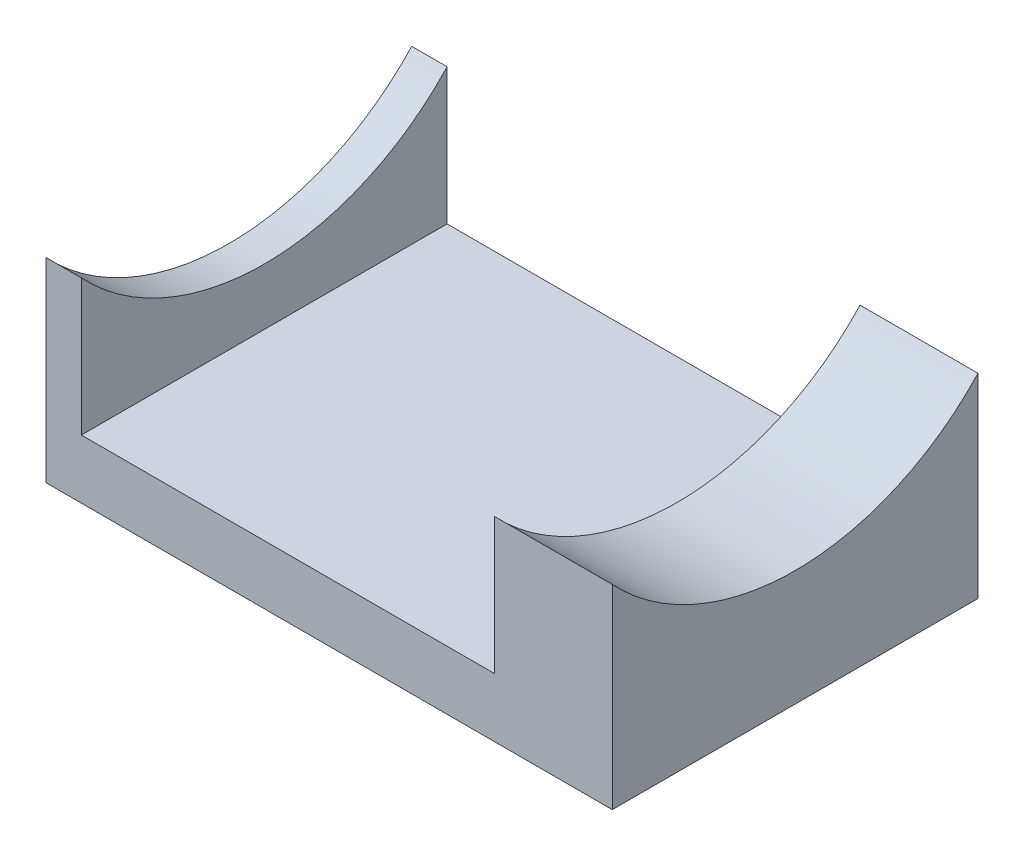
SolidWorks part; units mm, degrees
ref_plane "Piano frontale" through (0, 0, 0) normal (0, 0, 1) x (1, 0, 0)
ref_plane "Piano superiore" through (0, 0, 0) normal (0, 1, 0) x (1, 0, 0)
ref_plane "Piano destro" through (0, 0, 0) normal (1, 0, 0) x (0, 0, -1)
sketch "Schizzo1" plane through (0, 0, 0) normal (0, 0, 1) x (1, 0, 0)
  line L1 (-24, -15.5) -> (24, -15.5)
  line L2 (-24, -15.5) -> (-24, 15.5)
  line L3 (-24, 15.5) -> (24, 15.5)
  line L4 (24, -15.5) -> (24, 15.5)
  line L5 (-24, -15.5) -> (24, 15.5) construction
  line L6 (-24, 15.5) -> (24, -15.5) construction
  point P0 (0, 0)
  point P4 (0, 0)
  dimension "D1" = 48
  dimension "D2" = 31
extrude "Estrusione-Estrusione1" add sketch "Schizzo1" along normal mid plane 31
sketch "Schizzo2" plane through (0, 0, 15.5) normal (0, 0, 1) x (1, 0, 0)
  line L0 (24, 15.5) -> (-24, 15.5) construction
  line L1 (-21, 15.5) -> (14, 15.5)
  line L2 (-21, 15.5) -> (-21, -10.5)
  line L3 (-21, -10.5) -> (14, -10.5)
  line L4 (14, 15.5) -> (14, -10.5)
  line L5 (-24, -15.5) -> (24, -15.5) construction
  line L6 (-24, 15.5) -> (-24, -15.5) construction
  line L7 (24, -15.5) -> (24, 15.5) construction
  dimension "D1" = 5
  dimension "D2" = 3
  dimension "D3" = 10
extrude "Taglio-Estrusione1" cut sketch "Schizzo2" against normal up to next
sketch "Schizzo3" plane through (24, 0, 0) normal (1, 0, 0) x (0, 0, -1)
  line L0 (-15.5, 15.5) -> (15.5, 15.5) construction
  circle A0 centre (0, 15.5) radius 21.2
  dimension "D1" = 42.4
extrude "Taglio-Estrusione2" cut sketch "Schizzo3" against normal through all
sketch "Schizzo5" plane through (0, 0, 0) normal (0, 0, 1) x (1, 0, 0)
  line L0 (-24, -15.5) -> (24, -15.5) construction
  line L1 (9, -15.5) -> (11.5, -15.5)
  line L2 (9, -15.5) -> (9, -20.5)
  line L3 (9, -20.5) -> (11.5, -20.5)
  line L4 (11.5, -15.5) -> (11.5, -20.5)
  line L5 (24, -15.5) -> (24, 1.0366) construction
  dimension "D1" = 5
  dimension "D2" = 2.5
  dimension "D3" = 15
revolve "Rivoluzione2" add sketch "Schizzo5" angle 360 about L2
pattern_linear "Ripetizione a L1" count 2 spacing 20 along (-1, 0, 0) of "Rivoluzione2"
